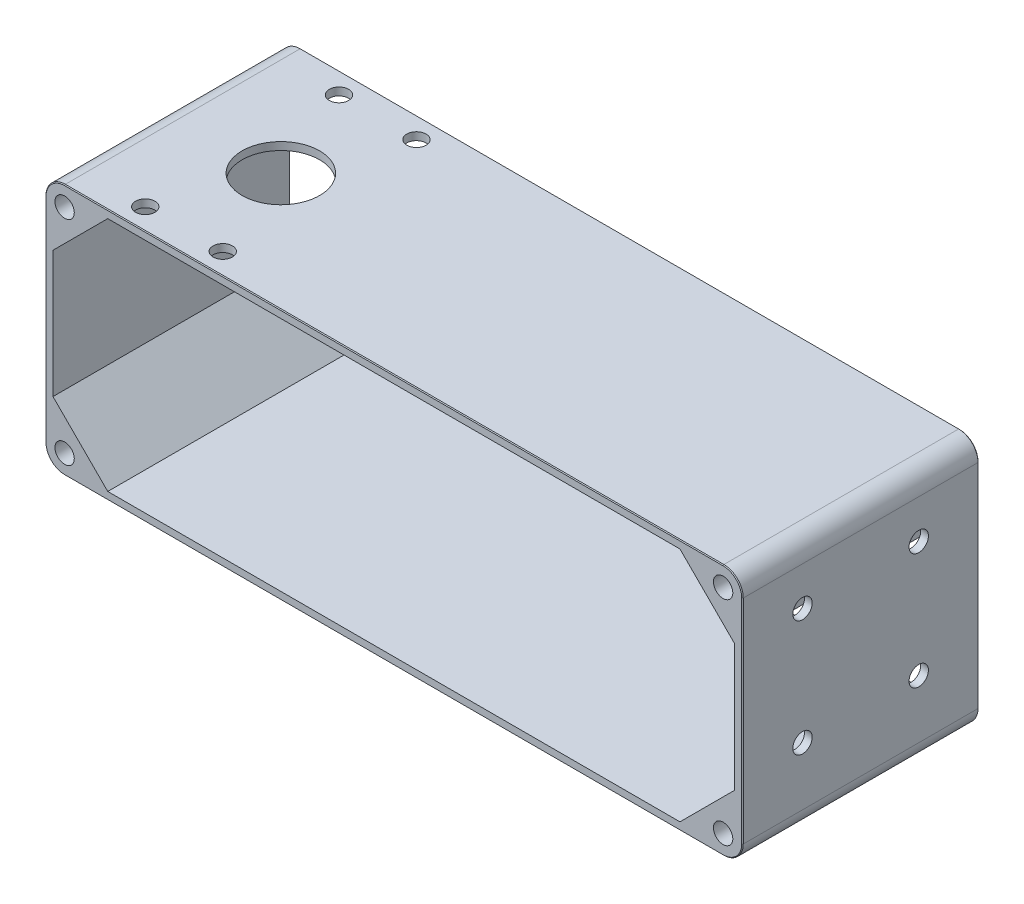
SolidWorks part; units mm, degrees
ref_plane "Front Plane" through (0, 0, 0) normal (0, 0, 1) x (1, 0, 0)
ref_plane "Top Plane" through (0, 0, 0) normal (0, 1, 0) x (1, 0, 0)
ref_plane "Right Plane" through (0, 0, 0) normal (1, 0, 0) x (0, 0, -1)
sketch "Sketch3" plane through (0, 0, 0) normal (0, 0, 1) x (1, 0, 0)
  line L0 (-15.875, 5.7326) -> (15.875, 5.7326) construction
  line L1 (107.95, -41.275) -> (-107.95, -41.275)
  line L2 (114.3, -34.925) -> (114.3, 34.925)
  line L3 (107.95, 41.275) -> (-107.95, 41.275)
  line L4 (-114.3, -34.925) -> (-114.3, 34.925)
  line L5 (114.3, -41.275) -> (-114.3, 41.275) construction
  line L6 (114.3, 41.275) -> (-114.3, -41.275) construction
  line L12 (72.898, 12.7) -> (72.898, -12.7) construction
  line L13 (72.898, -12.7) -> (98.298, -12.7) construction
  line L14 (98.298, -12.7) -> (98.298, 12.7) construction
  line L15 (98.298, 12.7) -> (72.898, 12.7) construction
  line L16 (72.898, 12.7) -> (98.298, -12.7) construction
  line L17 (98.298, 12.7) -> (72.898, -12.7) construction
  line L18 (-98.298, 12.7) -> (-72.898, 12.7) construction
  line L19 (-72.898, 12.7) -> (-72.898, -12.7) construction
  line L20 (-72.898, -12.7) -> (-98.298, -12.7) construction
  line L21 (-98.298, -12.7) -> (-98.298, 12.7) construction
  line L22 (-98.298, 12.7) -> (-72.898, -12.7) construction
  line L23 (-72.898, 12.7) -> (-98.298, -12.7) construction
  line L24 (-15.875, -5.7326) -> (15.875, 5.7326) construction
  line L25 (-15.875, 5.7326) -> (15.875, -5.7326) construction
  line L26 (15.875, 5.7326) -> (15.875, -5.7326) construction
  line L27 (15.875, -5.7326) -> (-15.875, -5.7326) construction
  line L28 (-15.875, -5.7326) -> (-15.875, 5.7326) construction
  line L29 (-15.875, 5.7326) -> (15.875, -5.7326) construction
  line L30 (15.875, 5.7326) -> (-15.875, -5.7326) construction
  arc A0 (114.3, 34.925) -> (107.95, 41.275) centre (107.95, 34.925) ccw
  arc A1 (107.95, -41.275) -> (114.3, -34.925) centre (107.95, -34.925) ccw
  arc A2 (-107.95, -41.275) -> (-114.3, -34.925) centre (-107.95, -34.925) cw
  arc A3 (-107.95, 41.275) -> (-114.3, 34.925) centre (-107.95, 34.925) ccw
  circle A8 centre (-107.95, 34.925) radius 3.175
  circle A9 centre (-107.95, -34.925) radius 3.175
  circle A10 centre (107.95, -34.925) radius 3.175
  circle A11 centre (107.95, 34.925) radius 3.175
  circle A24 centre (-85.598, 0) radius 3.429
  circle A25 centre (85.598, 0) radius 3.429
  circle A26 centre (-15.875, 5.7326) radius 3.175
  circle A27 centre (15.875, 5.7326) radius 3.175
  circle A28 centre (15.875, -5.7326) radius 3.175
  circle A29 centre (-15.875, -5.7326) radius 3.175
  point P0 (0, 0)
  point P22 (-114.3, 0)
  point P23 (0, 0)
  point P57 (-98.298, 0)
  dimension "D3" = 6.35
  dimension "D6" = 16.002
  dimension "D7" = 6.35
  dimension "D8" = 16.002
  dimension "D9" = 28.575
  dimension "D10" = 31.75
  dimension "D11" = 6.35
  dimension "D14" = 25.4
  dimension "D4" = 6.858
  dimension "D5" = 6.858
  dimension "D1" = 82.55
  dimension "D2" = 228.6
  dimension "D12" = 25.4
extrude "Boss-Extrude1" add sketch "Sketch3" along normal blind 77.47
sketch "Sketch4" plane through (0, 0, 77.47) normal (0, 0, 1) x (1, 0, 0)
  line L0 (107.95, 38.735) -> (-107.95, 38.735)
  line L1 (-111.76, 34.925) -> (-111.76, -34.925)
  line L2 (-107.95, -38.735) -> (107.95, -38.735)
  line L3 (111.76, -34.925) -> (111.76, 34.925)
  line L4 (107.95, 41.275) -> (-107.95, 41.275)
  line L5 (-114.3, 34.925) -> (-114.3, -34.925)
  line L6 (-107.95, -41.275) -> (107.95, -41.275)
  line L7 (114.3, -34.925) -> (114.3, 34.925)
  line L8 (107.95, 41.275) -> (-107.95, 41.275)
  line L9 (-114.3, 34.925) -> (-114.3, -34.925)
  line L10 (-107.95, -41.275) -> (107.95, -41.275)
  line L11 (114.3, -34.925) -> (114.3, 34.925)
  line L12 (-111.76, 20.7745) -> (-93.7995, 38.735)
  line L13 (-111.76, -20.7745) -> (-93.7995, -38.735)
  line L14 (93.7995, -38.735) -> (111.76, -20.7745)
  line L15 (111.76, 20.7745) -> (93.7995, 38.735)
  arc A0 (111.76, 34.925) -> (107.95, 38.735) centre (107.95, 34.925) ccw
  arc A1 (-107.95, 38.735) -> (-111.76, 34.925) centre (-107.95, 34.925) ccw
  arc A2 (-111.76, -34.925) -> (-107.95, -38.735) centre (-107.95, -34.925) ccw
  arc A3 (107.95, -38.735) -> (111.76, -34.925) centre (107.95, -34.925) ccw
  arc A4 (114.3, 34.925) -> (107.95, 41.275) centre (107.95, 34.925) ccw
  arc A5 (-107.95, 41.275) -> (-114.3, 34.925) centre (-107.95, 34.925) ccw
  arc A6 (-114.3, -34.925) -> (-107.95, -41.275) centre (-107.95, -34.925) ccw
  arc A7 (107.95, -41.275) -> (114.3, -34.925) centre (107.95, -34.925) ccw
  arc A8 (114.3, 34.925) -> (107.95, 41.275) centre (107.95, 34.925) ccw
  arc A9 (-107.95, 41.275) -> (-114.3, 34.925) centre (-107.95, 34.925) ccw
  arc A10 (-114.3, -34.925) -> (-107.95, -41.275) centre (-107.95, -34.925) ccw
  arc A11 (107.95, -41.275) -> (114.3, -34.925) centre (107.95, -34.925) ccw
  circle M19 centre (-85.598, 0) radius 3.429
  circle M28 centre (85.598, 0) radius 3.429
  circle M39 centre (15.875, -5.7326) radius 3.175
  circle M40 centre (-15.875, 5.7326) radius 3.175
  circle M41 centre (15.875, 5.7326) radius 3.175
  circle M42 centre (-15.875, -5.7326) radius 3.175
  dimension "D3" = 45
  dimension "D4" = 45
  dimension "D5" = 45
  dimension "D6" = 45
  dimension "D7" = 25.4
  dimension "D1" = 0
  dimension "D2" = 2.54
chamfer "Chamfer1" distance 0.254 angle 45 16 edges at (0, 41.275, 0) (-112.4401, 39.4151, 0) (-114.3, 0, 0) (-112.4401, -39.4151, 0) (0, -41.275, 0) (112.4401, -39.4151, 0) (114.3, 0, 0) (112.4401, 39.4151, 0) (0, 41.275, 77.47) (-112.4401, 39.4151, 77.47) (112.4401, 39.4151, 77.47) (-114.3, 0, 77.47) (114.3, 0, 77.47) (-112.4401, -39.4151, 77.47) (112.4401, -39.4151, 77.47) (0, -41.275, 77.47)
extrude "Cut-Extrude1" cut sketch "Sketch4" against normal through all both and the other way through all contours L3 L15 L0 L12 L1 L13 L2 L14 M39 M19 M28 M42 M41 M40
sketch "Sketch5" plane through (0, 41.275, 0) normal (0, 1, 0) x (1, 0, 0)
  line L0 (-107.95, -77.47) -> (107.95, 0) construction
  line L1 (107.95, -77.47) -> (-107.95, 0) construction
  line L2 (-88.4836, -6.985) -> (-88.4836, -70.485) construction
  line L3 (-88.4836, -70.485) -> (-63.0836, -70.485) construction
  line L4 (-63.0836, -70.485) -> (-63.0836, -6.985) construction
  line L5 (-63.0836, -6.985) -> (-88.4836, -6.985) construction
  line L8 (-88.4836, -6.985) -> (-63.0836, -70.485) construction
  line L9 (-88.4836, -70.485) -> (-63.0836, -6.985) construction
  circle A0 centre (-88.4836, -6.985) radius 3.175
  circle A1 centre (-63.0836, -6.985) radius 3.175
  circle A2 centre (-63.0836, -70.485) radius 3.175
  circle A3 centre (-88.4836, -70.485) radius 3.175
  circle A4 centre (-75.7836, -38.735) radius 12.7
  dimension "D3" = 6.35
  dimension "D1" = 63.5
  dimension "D2" = 25.4
extrude "Cut-Extrude2" cut sketch "Sketch5" against normal blind 2.54
sketch "Sketch6" plane through (114.3, 0, 0) normal (1, 0, 0) x (0, 0, -1)
  line L0 (-57.785, 22.225) -> (-57.785, -15.875) construction
  line L1 (-57.785, -15.875) -> (-19.685, -15.875) construction
  line L2 (-19.685, -15.875) -> (-19.685, 22.225) construction
  line L3 (-19.685, 22.225) -> (-57.785, 22.225) construction
  line L4 (-57.785, 22.225) -> (-19.685, -15.875) construction
  line L5 (-19.685, 22.225) -> (-57.785, -15.875) construction
  line L6 (-77.216, 34.925) -> (-0.254, 34.925) construction
  circle A0 centre (-57.785, 22.225) radius 3.175
  circle A1 centre (-19.685, 22.225) radius 3.175
  circle A2 centre (-19.685, -15.875) radius 3.175
  circle A3 centre (-57.785, -15.875) radius 3.175
  point P10 (-38.735, 34.925)
  point P11 (-38.735, 3.175)
  dimension "D1" = 6.35
  dimension "D2" = 38.1
  dimension "D3" = 38.1
  dimension "D4" = 12.7
extrude "Cut-Extrude3" cut sketch "Sketch6" against normal blind 2.54
